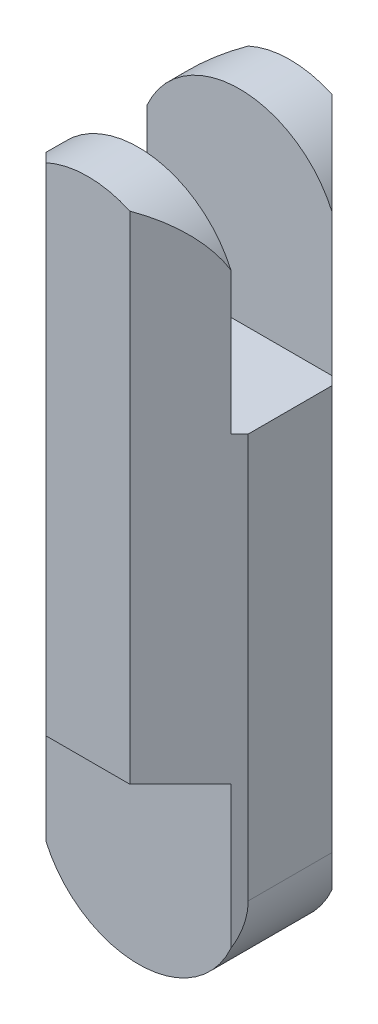
SolidWorks part; units mm, degrees
ref_plane "Front" through (0, 0, 0) normal (0, 0, 1) x (1, 0, 0)
ref_plane "Top" through (0, 0, 0) normal (0, 1, 0) x (1, 0, 0)
ref_plane "Right" through (0, 0, 0) normal (1, 0, 0) x (0, 0, -1)
sketch "草图1" plane through (0, 0, 0) normal (0, 1, 0) x (1, 0, 0)
  line L0 (-12.6518, 0) -> (13.462, 0) construction
  line L1 (0, 11.6722) -> (0, -14.1269) construction
  line L3 (10, 4.1421) -> (4.1421, 10)
  line L4 (4.1421, 10) -> (-4.1421, 10)
  line L5 (-4.1421, 10) -> (-10, 4.1421)
  line L6 (-10, 4.1421) -> (-10, -4.1421)
  line L7 (-10, -4.1421) -> (-4.1421, -10)
  line L8 (-4.1421, -10) -> (4.1421, -10)
  line L9 (4.1421, -10) -> (10, -4.1421)
  line L10 (10, -4.1421) -> (10, 4.1421)
  circle A0 centre (0, 0) radius 10 construction
extrude "凸台-拉伸1" add sketch "草图1" along normal blind 70
sketch "草图2" plane through (0, 0, 10) normal (0, 0, 1) x (1, 0, 0)
  line L0 (0, 0) -> (0, 24) construction
  line L7 (-10, 10) -> (-10, -2.3893)
  line L8 (-10, -2.3893) -> (10, -2.3893)
  line L9 (10, 10) -> (10, -2.3893)
  arc A1 (-10, 10) -> (10, 10) centre (0, 10) ccw
extrude "切除-拉伸1" cut sketch "草图2" against normal blind 66
sketch "草图4" plane through (0, 0, 10) normal (0, 0, 1) x (1, 0, 0)
  line L0 (10, 70) -> (10, 10) construction
  line L2 (-10, 10) -> (-10, 20)
  line L3 (-10, 20) -> (10, 20)
  line L4 (10, 10) -> (10, 20)
  arc A0 (-10, 10) -> (10, 10) centre (0, 10) ccw
extrude "切除-拉伸2" cut sketch "草图4" against normal blind 5
sketch "草图5" plane through (0, 0, -10) normal (0, 0, -1) x (-1, 0, 0)
  line L0 (10, 70) -> (10, 10) construction
  line L2 (-10, 10) -> (-10, 20)
  line L3 (-10, 20) -> (10, 20)
  line L4 (10, 10) -> (10, 20)
  arc A0 (-10, 10) -> (10, 10) centre (0, 10) ccw
extrude "切除-拉伸3" cut sketch "草图5" against normal blind 5
sketch "草图6" plane through (0, 0, 0) normal (0, 0, 1) x (1, 0, 0)
  line L0 (0, 70) -> (0, 0) construction
  line L1 (-4.1421, 70) -> (4.1421, 70) construction
  line L2 (10, 70) -> (10, 10) construction
  line L3 (-10, 70) -> (10, 70)
  line L4 (-10, 70) -> (-10, 50)
  line L5 (-10, 50) -> (10, 50)
  line L6 (10, 70) -> (10, 50)
  dimension "D1" = 20
extrude "切除-拉伸4" cut sketch "草图6" against normal mid plane 10
sketch "草图7" plane through (0, 0, 10) normal (0, 0, 1) x (1, 0, 0)
  line L0 (0, 70) -> (0, 0) construction
  line L1 (-4.1421, 70) -> (4.1421, 70) construction
  line L4 (-10, 60) -> (-10, 77.826)
  line L5 (-10, 77.826) -> (10, 77.826)
  line L6 (10, 60) -> (10, 77.826)
  arc A0 (10, 60) -> (-10, 60) centre (0, 60) ccw
extrude "切除-拉伸5" cut sketch "草图7" against normal blind 30
